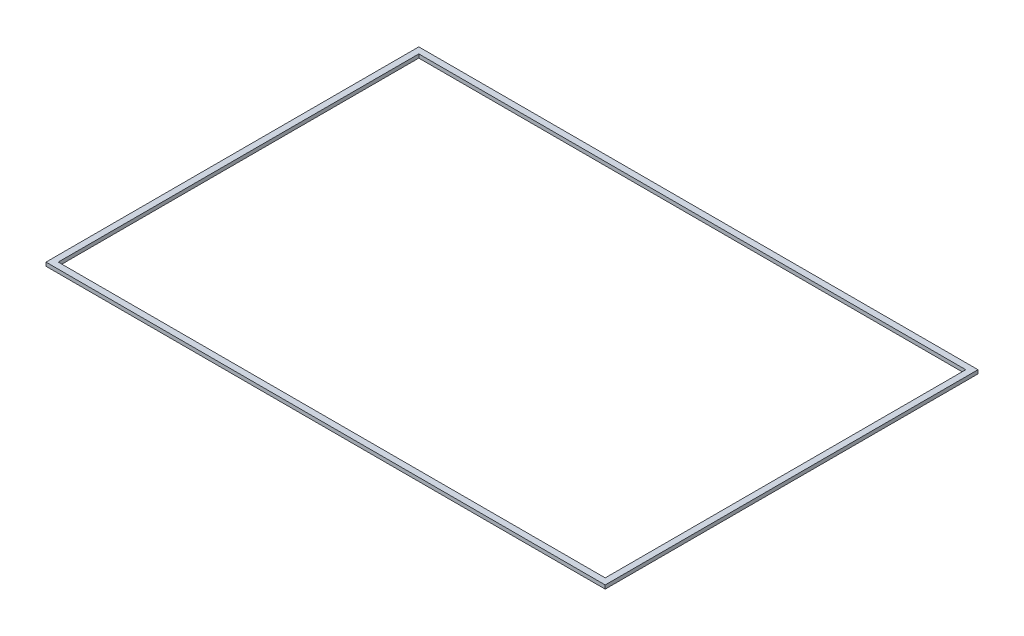
SolidWorks part; units mm, degrees
ref_plane "Спереди" through (0, 0, 0) normal (0, 0, 1) x (1, 0, 0)
ref_plane "Сверху" through (0, 0, 0) normal (0, 1, 0) x (1, 0, 0)
ref_plane "Справа" through (0, 0, 0) normal (1, 0, 0) x (0, 0, -1)
ref_plane "Плоскость4"
sketch "Эскиз1" plane through (0, 0, 0) normal (0, 1, 0) x (-1, 0, 0)
  line L0 (915, -610) -> (915, -300)
  line L1 (915, -300) -> (895, -300)
  line L2 (895, -300) -> (895, -590)
  line L3 (895, -590) -> (-895, -590)
  line L4 (-895, -590) -> (-895, -300)
  line L5 (-895, -300) -> (-915, -300)
  line L6 (-915, -300) -> (-915, -610)
  line L7 (-915, -610) -> (915, -610)
  line L8 (895, 590) -> (895, 300)
  line L9 (895, 300) -> (915, 300)
  line L10 (915, 300) -> (915, 610)
  line L11 (915, 610) -> (-915, 610)
  line L12 (-915, 610) -> (-915, 300)
  line L13 (-915, 300) -> (-895, 300)
  line L14 (-895, 300) -> (-895, 590)
  line L15 (-895, 590) -> (895, 590)
  line L16 (-915, 300) -> (-915, -300)
  line L17 (-915, -300) -> (-895, -300)
  line L18 (-895, -300) -> (-895, 300)
  line L19 (-895, 300) -> (-915, 300)
  line L20 (895, 300) -> (895, -300)
  line L21 (895, -300) -> (915, -300)
  line L22 (915, -300) -> (915, 300)
  line L23 (915, 300) -> (895, 300)
  dimension "D1" = 1830
  dimension "D2" = 1220
  dimension "D3" = 600
extrude "Выдавливание1" add sketch "Эскиз1" along normal blind 12 contours L6 L7 L0 L1 L2 L3 L4 L5 | L14 L15 L8 L9 L10 L11 L12 L13 | L5 L18 L13 L16 | L1 L22 L9 L20
